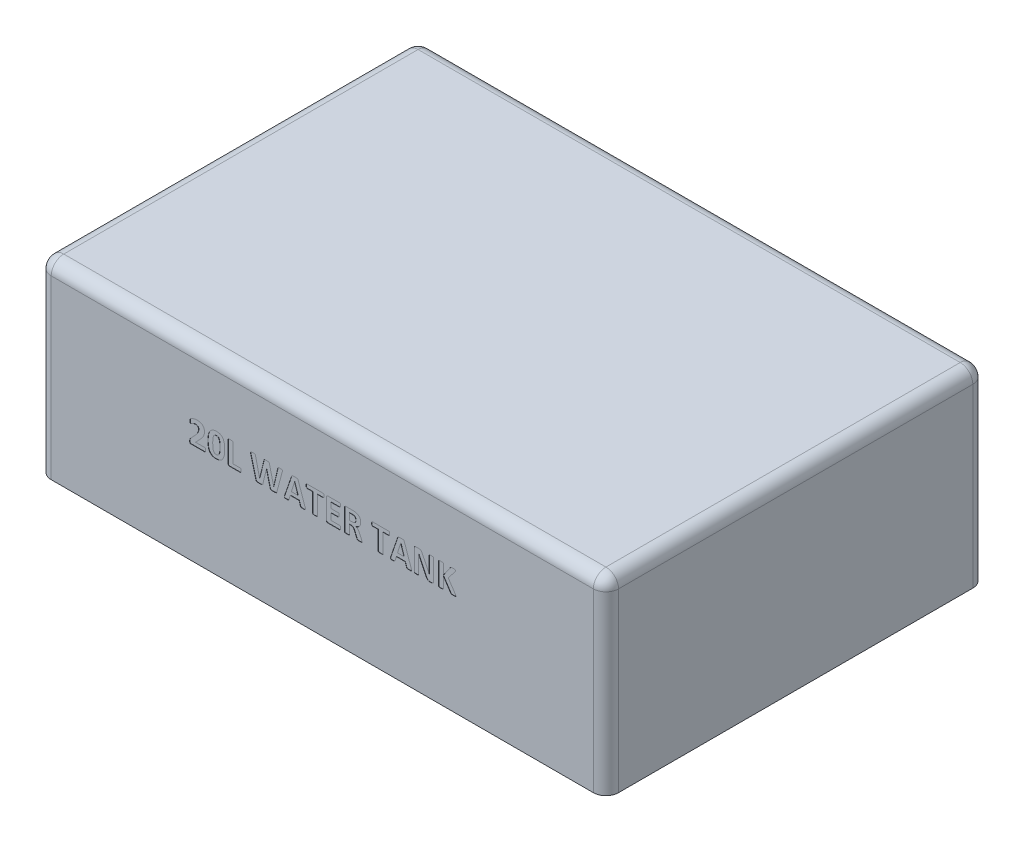
SolidWorks part; units mm, degrees
other "Markup1"
sketch "Sketch10" plane through (150, 350, 101) normal (0.9279, 0.2672, 0.26) x (0.2821, -0.0471, -0.9582)
sketch "Sketch11" plane through (150, 350, 101) normal (0.9279, 0.2672, 0.26) x (0.2821, -0.0471, -0.9582)
material "ABS PC"
ref_plane "Front Plane" through (0, 0, 0) normal (0, 0, 1) x (1, 0, 0)
ref_plane "Top Plane" through (0, 0, 0) normal (0, 1, 0) x (1, 0, 0)
ref_plane "Right Plane" through (0, 0, 0) normal (1, 0, 0) x (0, 0, -1)
sketch "Sketch1" plane through (0, 0, 0) normal (0, 1, 0) x (1, 0, 0)
  line L1 (-225, 150) -> (225, 150)
  line L2 (-225, 150) -> (-225, -150)
  line L3 (-225, -150) -> (225, -150)
  line L4 (225, 150) -> (225, -150)
  line L5 (-225, 150) -> (225, -150) construction
  line L6 (-225, -150) -> (225, 150) construction
  point P0 (0, 0)
  dimension "D1" = 450
  dimension "D2" = 300
extrude "Boss-Extrude1" add sketch "Sketch1" along normal blind 150
sketch "Sketch6" plane through (0, 0, 150) normal (0, 0, 1) x (1, 0, 0)
  line L1 (-225, 150) -> (225, 150)
  line L2 (-225, 150) -> (-225, 0)
  line L3 (-225, 0) -> (225, 0)
  line L4 (225, 150) -> (225, 0)
extrude "Boss-Extrude3" add sketch "Sketch6" along normal blind 1
sketch "Sketch7" plane through (0, 0, 151) normal (0, 0, 1) x (1, 0, 0)
  line L0 (-225, 80) -> (225, 80) construction
  line L1 (-225, 150) -> (-225, 0) construction
  line L2 (225, 0) -> (225, 150) construction
  line L3 (-225, 0) -> (225, 0) construction
  text T0 "20L WATER TANK" font "Calibri" height in points 70
  dimension "D1" = 80
extrude "Cut-Extrude4" cut sketch "Sketch7" against normal blind 0.2
fillet "Fillet2" radius 10 8 edges at (0, 150, 151) (-225, 150, 0.5) (0, 150, -150) (225, 150, 0.5) (-225, 75, -150) (225, 75, -150) (225, 75, 151) (-225, 75, 151)
sketch "Sketch12" plane through (225, 0, 0) normal (1, 0, 0) x (0, 0, -1)
  line L0 (-141, 0) -> (140, 0) construction
  line L1 (150, 140) -> (150, 0) construction
  circle A0 centre (120, 20) radius 15
  dimension "D1" = 30
  dimension "D2" = 20
  dimension "D3" = 30
